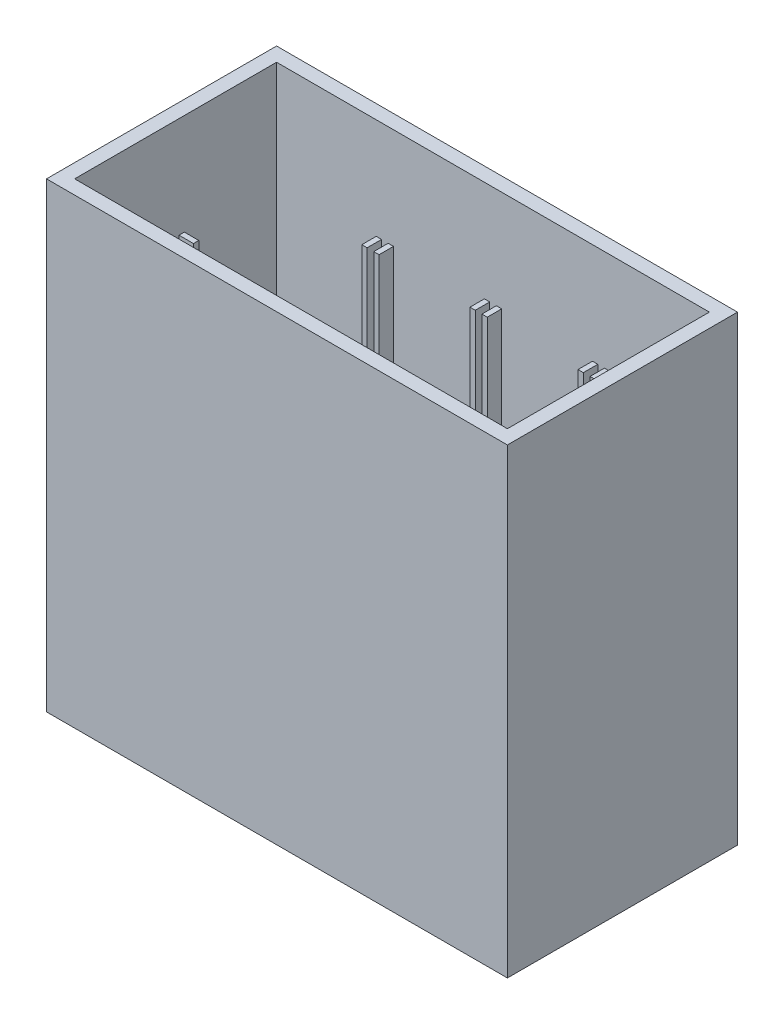
SolidWorks part; units mm, degrees
ref_plane "Front Plane" through (0, 0, 0) normal (0, 0, 1) x (1, 0, 0)
ref_plane "Top Plane" through (0, 0, 0) normal (0, 1, 0) x (1, 0, 0)
ref_plane "Right Plane" through (0, 0, 0) normal (1, 0, 0) x (0, 0, -1)
sketch "Sketch1" plane through (0, 0, 0) normal (0, 1, 0) x (1, 0, 0)
  line L1 (-79.875, 39.875) -> (79.875, 39.875)
  line L2 (-79.875, 39.875) -> (-79.875, -39.875)
  line L3 (-79.875, -39.875) -> (79.875, -39.875)
  line L4 (79.875, 39.875) -> (79.875, -39.875)
  line L5 (-79.875, 39.875) -> (79.875, -39.875) construction
  line L6 (-79.875, -39.875) -> (79.875, 39.875) construction
  point P0 (0, 0)
  dimension "D1" = 79.75
  dimension "D2" = 159.75
extrude "Boss-Extrude1" add sketch "Sketch1" along normal blind 225
sketch "Sketch2" plane through (0, 225, 0) normal (0, 1, 0) x (1, 0, 0)
  line L1 (-75, 35) -> (75, 35)
  line L2 (-75, 35) -> (-75, -35)
  line L3 (-75, -35) -> (75, -35)
  line L4 (75, 35) -> (75, -35)
  line L5 (-75, 35) -> (75, -35) construction
  line L6 (-75, -35) -> (75, 35) construction
  point P0 (0, 0)
  dimension "D1" = 150
  dimension "D2" = 70
extrude "Cut-Extrude1" cut sketch "Sketch2" against normal blind 220
sketch "Sketch7" plane through (0, 0, 35) normal (0, 0, -1) x (-1, 0, 0)
  line L0 (-79.875, 225) -> (-79.875, 0) construction
  line L1 (-40.475, 125) -> (-34.475, 125)
  line L2 (-40.475, 125) -> (-40.475, 5)
  line L3 (-40.475, 5) -> (-34.475, 5)
  line L4 (-34.475, 125) -> (-34.475, 5)
  line L5 (-40.475, 125) -> (-34.475, 5) construction
  line L6 (-40.475, 5) -> (-34.475, 125) construction
  line L7 (0, -8.2288) -> (0, 17.5288) construction
  line L8 (40.475, 5) -> (34.475, 5)
  line L9 (34.475, 125) -> (34.475, 5)
  line L10 (40.475, 125) -> (40.475, 5)
  line L11 (40.475, 125) -> (34.475, 125)
  line L12 (-2.975, 125) -> (-2.975, 5)
  line L13 (-2.975, 125) -> (3.025, 125)
  line L14 (3.025, 125) -> (3.025, 5)
  line L15 (-2.975, 5) -> (3.025, 5)
  line L16 (-1.1, 125) -> (-1.1, 5)
  line L17 (-38.6, 125) -> (-36.35, 125)
  line L18 (-38.6, 125) -> (-38.6, 5)
  line L19 (-38.6, 5) -> (-36.35, 5)
  line L20 (-36.35, 125) -> (-36.35, 5)
  line L21 (-38.6, 125) -> (-36.35, 5) construction
  line L22 (-38.6, 5) -> (-36.35, 125) construction
  line L23 (-1.1, 125) -> (1.15, 125)
  line L24 (1.15, 125) -> (1.15, 5)
  line L25 (-1.1, 5) -> (1.15, 5)
  line L26 (36.35, 125) -> (36.35, 5)
  line L27 (38.6, 125) -> (38.6, 5)
  line L28 (-79.875, 0) -> (79.875, 0) construction
  point P0 (-37.475, 65)
  point P15 (-37.475, 65)
  dimension "D1" = 6
  dimension "D2" = 120
  dimension "D3" = 42.4
  dimension "D5" = 120
  dimension "D6" = 2.25
  dimension "D7" = 2
  dimension "D8" = 5
  dimension "D9" = 31.5
  dimension "D10" = 1.875
  dimension "D4" = 2
extrude "Boss-Extrude2" add sketch "Sketch7" along normal blind 5 contours L18 L1 L2 L3 | L1 L20 L3 L4 | L16 L13 L12 L15 | L13 L24 L15 L14 | L26 L11 L9 L8 | L11 L27 L8 L10
sketch "Sketch8" plane through (0, 0, -35) normal (0, 0, 1) x (1, 0, 0)
  line L0 (-79.875, 0) -> (79.875, 0) construction
  line L1 (-38.625, 125) -> (-36.325, 125)
  line L2 (-38.625, 125) -> (-38.625, 5)
  line L3 (-38.625, 5) -> (-36.325, 5)
  line L4 (-36.325, 125) -> (-36.325, 5)
  line L5 (-38.625, 125) -> (-36.325, 5) construction
  line L6 (-38.625, 5) -> (-36.325, 125) construction
  line L7 (-40.475, 125) -> (-34.475, 125)
  line L8 (-40.475, 125) -> (-40.475, 5)
  line L9 (-40.475, 5) -> (-34.475, 5)
  line L10 (-34.475, 125) -> (-34.475, 5)
  line L11 (-40.475, 125) -> (-34.475, 5) construction
  line L12 (-40.475, 5) -> (-34.475, 125) construction
  line L13 (0, 0) -> (0, 25.2888) construction
  line L14 (38.625, 125) -> (36.325, 125)
  line L15 (40.475, 125) -> (34.475, 125)
  line L16 (40.475, 5) -> (34.475, 5)
  line L17 (38.625, 5) -> (36.325, 5)
  line L18 (34.475, 125) -> (34.475, 5)
  line L19 (36.325, 125) -> (36.325, 5)
  line L20 (38.625, 125) -> (38.625, 5)
  line L21 (40.475, 125) -> (40.475, 5)
  line L22 (-2.975, 125) -> (-2.975, 5)
  line L23 (-2.975, 125) -> (3.025, 125)
  line L24 (3.025, 125) -> (3.025, 5)
  line L25 (-2.975, 5) -> (3.025, 5)
  line L26 (-1.125, 125) -> (-1.125, 5)
  line L27 (-1.125, 125) -> (1.175, 125)
  line L28 (1.175, 125) -> (1.175, 5)
  line L29 (-1.125, 5) -> (1.175, 5)
  line L33 (-79.875, 225) -> (-79.875, 0) construction
  point P0 (-37.475, 65)
  point P5 (-37.475, 65)
  line M22 (-75, 5) -> (75, 5)
  dimension "D1" = 120
  dimension "D2" = 5
  dimension "D3" = 2.3
  dimension "D4" = 6
  dimension "D6" = 42.4
  dimension "D7" = 31.5
  dimension "D5" = 2
extrude "Boss-Extrude3" add sketch "Sketch8" along normal blind 5 contours L7 L8 L2 M22 | L10 L7 L4 M22 | L26 L23 L22 M22 | L23 L28 L24 M22 | L19 L15 L18 M22 | L21 L15 L20 M22
sketch "Sketch9" plane through (-75, 0, 0) normal (1, 0, 0) x (0, 0, -1)
  line L0 (-39.875, 0) -> (39.875, 0) construction
  line L1 (-2.975, 125) -> (3.025, 125)
  line L2 (-2.975, 125) -> (-2.975, 5)
  line L3 (-2.975, 5) -> (3.025, 5)
  line L4 (3.025, 125) -> (3.025, 5)
  line L5 (-2.975, 125) -> (3.025, 5) construction
  line L6 (-2.975, 5) -> (3.025, 125) construction
  line L7 (-39.875, 225) -> (-39.875, 0) construction
  line L9 (-1.125, 125) -> (1.175, 125)
  line L10 (-1.125, 125) -> (-1.125, 5)
  line L11 (-1.125, 5) -> (1.175, 5)
  line L12 (1.175, 125) -> (1.175, 5)
  line L13 (-1.125, 125) -> (1.175, 5) construction
  line L14 (-1.125, 5) -> (1.175, 125) construction
  point P0 (0.025, 65)
  point P7 (0.025, 65)
  line M7 (-35, 5) -> (35, 5)
  dimension "D1" = 6
  dimension "D2" = 120
  dimension "D3" = 65
  dimension "D4" = 39.9
  dimension "D5" = 2.3
  dimension "D6" = 120
extrude "Boss-Extrude4" add sketch "Sketch9" along normal blind 5 contours L10 L1 L2 M7 | L1 L12 L4 M7
sketch "Sketch10" plane through (75, 0, 0) normal (-1, 0, 0) x (0, 0, 1)
  line L0 (-39.875, 0) -> (39.875, 0) construction
  line L1 (-2.975, 125) -> (3.025, 125)
  line L2 (-2.975, 125) -> (-2.975, 5)
  line L3 (-2.975, 5) -> (3.025, 5)
  line L4 (3.025, 125) -> (3.025, 5)
  line L5 (-2.975, 125) -> (3.025, 5) construction
  line L6 (-2.975, 5) -> (3.025, 125) construction
  line L7 (-39.875, 225) -> (-39.875, 0) construction
  line L9 (-1.125, 125) -> (1.175, 125)
  line L10 (-1.125, 125) -> (-1.125, 5)
  line L11 (-1.125, 5) -> (1.175, 5)
  line L12 (1.175, 125) -> (1.175, 5)
  line L13 (-1.125, 125) -> (1.175, 5) construction
  line L14 (-1.125, 5) -> (1.175, 125) construction
  point P0 (0.025, 65)
  point P9 (0.025, 65)
  line M6 (-35, 5) -> (35, 5)
  dimension "D1" = 120
  dimension "D2" = 6
  dimension "D3" = 5
  dimension "D4" = 39.9
  dimension "D5" = 2.3
extrude "Boss-Extrude5" add sketch "Sketch10" along normal blind 5 contours L10 L1 L2 M6 | L1 L12 L4 M6
sketch "Sketch11" plane through (0, 225, 0) normal (0, 1, 0) x (1, 0, 0)
  line L1 (-79.875, 39.875) -> (79.875, 39.875)
  line L2 (-79.875, 39.875) -> (-79.875, -39.875)
  line L3 (-79.875, -39.875) -> (79.875, -39.875)
  line L4 (79.875, 39.875) -> (79.875, -39.875)
  line L5 (-75, 35) -> (75, 35)
  line L6 (-75, 35) -> (-75, -35)
  line L7 (-75, -35) -> (75, -35)
  line L8 (75, 35) -> (75, -35)
extrude "Cut-Extrude2" cut sketch "Sketch11" against normal blind 65 contours L2 L1 L4 L3 | L6 L5 L8 L7
